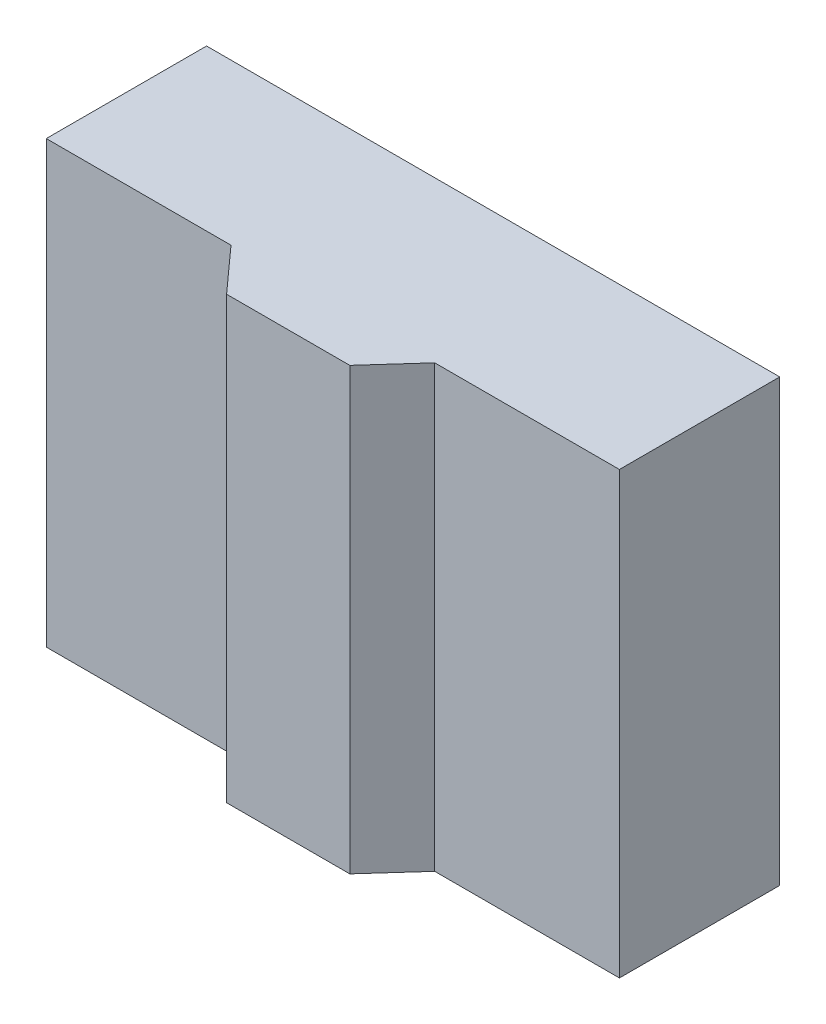
SolidWorks part; units mm, degrees
ref_plane "Front Plane" through (0, 0, 0) normal (0, 0, 1) x (1, 0, 0)
ref_plane "Top Plane" through (0, 0, 0) normal (0, 1, 0) x (1, 0, 0)
ref_plane "Right Plane" through (0, 0, 0) normal (1, 0, 0) x (0, 0, -1)
sketch "Sketch1" plane through (0, 0, 0) normal (0, 1, 0) x (1, 0, 0)
  line L0 (0, 36.9812) -> (0, 0)
  line L1 (0, 0) -> (42.6154, 0)
  line L2 (42.6154, 0) -> (51.8977, -10.3009)
  line L3 (51.8977, -10.3009) -> (80.325, -10.3009)
  line L4 (66.1114, -10.3009) -> (66.1114, 59.317) construction
  line L5 (89.6074, 0) -> (80.325, -10.3009)
  line L6 (132.2228, 0) -> (89.6074, 0)
  line L7 (132.2228, 36.9812) -> (132.2228, 0)
  line L8 (0, 36.9812) -> (132.2228, 36.9812)
extrude "Extrude1" add sketch "Sketch1" against normal blind 101.6
ref_plane "Plane1" through (0, 0, 25.4) normal (0, 0, 1) x (1, 0, 0)
sketch "Sketch2" plane through (0, 0, 25.4) normal (0, 0, 1) x (1, 0, 0)
  line L0 (51.8977, -50.8) -> (80.325, -50.8) construction
  line L1 (51.8977, -101.6) -> (51.8977, 0) construction
  line L2 (80.325, -101.6) -> (80.325, 0) construction
  circle A0 centre (66.1114, -50.8) radius 27.8057
